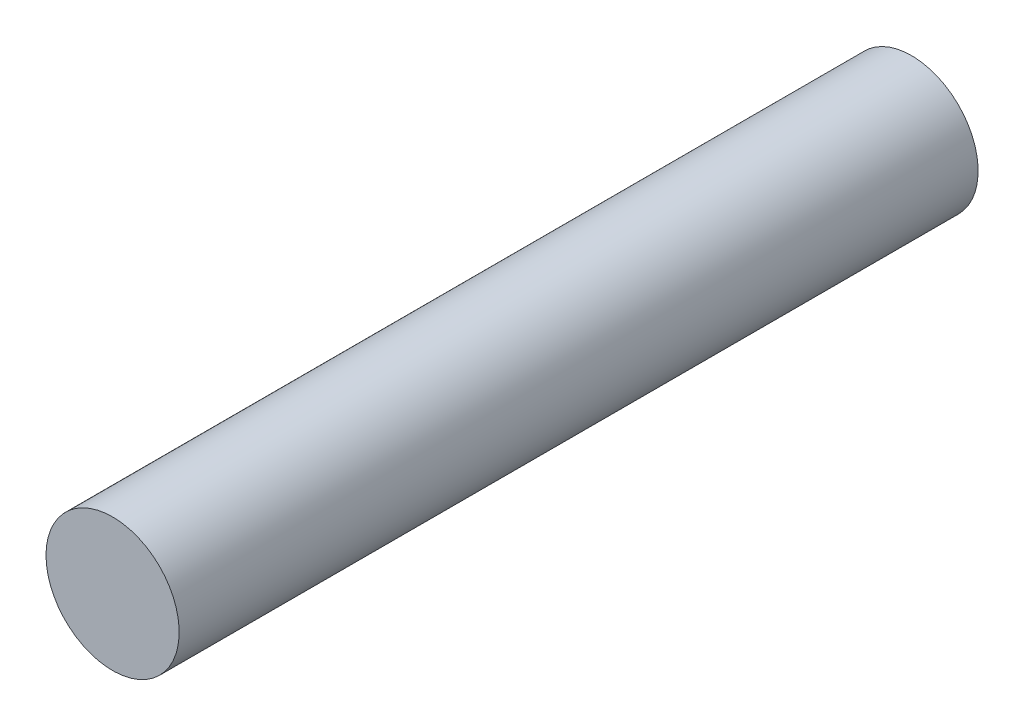
SolidWorks part; units mm, degrees
ref_plane "Plan de face" through (0, 0, 0) normal (0, 0, 1) x (1, 0, 0)
ref_plane "Plan de dessus" through (0, 0, 0) normal (0, 1, 0) x (1, 0, 0)
ref_plane "Plan de droite" through (0, 0, 0) normal (1, 0, 0) x (0, 0, -1)
sketch "Esquisse1" plane through (0, 0, 0) normal (0, 0, 1) x (1, 0, 0)
  circle A0 centre (0, 0) radius 3.175
  dimension "D1" = 6.35
extrude "Boss.-Extru.1" add sketch "Esquisse1" along normal blind 38.1
